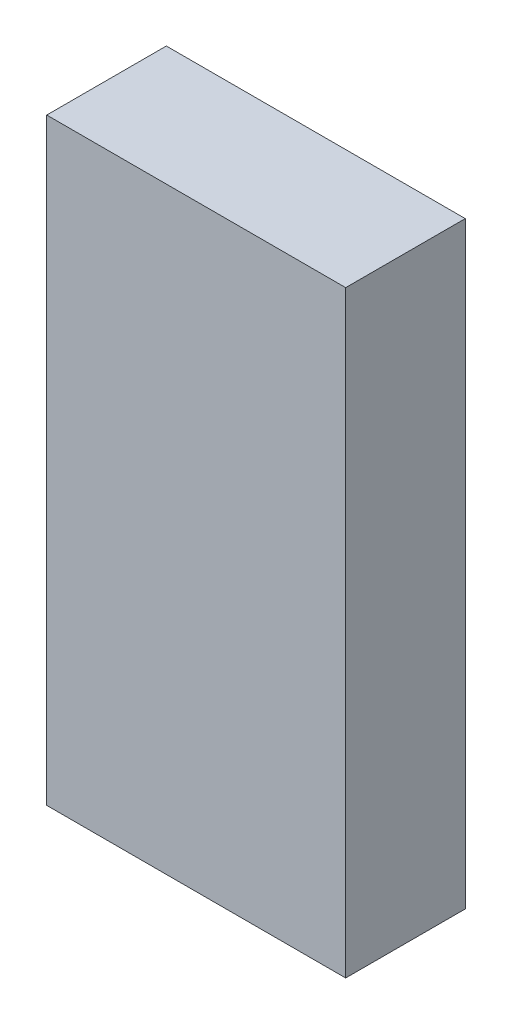
SolidWorks part; units mm, degrees
ref_plane "Front Plane" through (0, 0, 0) normal (0, 0, 1) x (1, 0, 0)
ref_plane "Top Plane" through (0, 0, 0) normal (0, 1, 0) x (1, 0, 0)
ref_plane "Right Plane" through (0, 0, 0) normal (1, 0, 0) x (0, 0, -1)
sketch "Sketch1" plane through (0, 0, 0) normal (0, 0, 1) x (1, 0, 0)
  line L1 (0, 0) -> (10, 0)
  line L2 (0, 0) -> (0, 20)
  line L3 (0, 20) -> (10, 20)
  line L4 (10, 0) -> (10, 20)
  dimension "D1" = 20
  dimension "D2" = 10
extrude "Boss-Extrude1" add sketch "Sketch1" along normal blind 4
